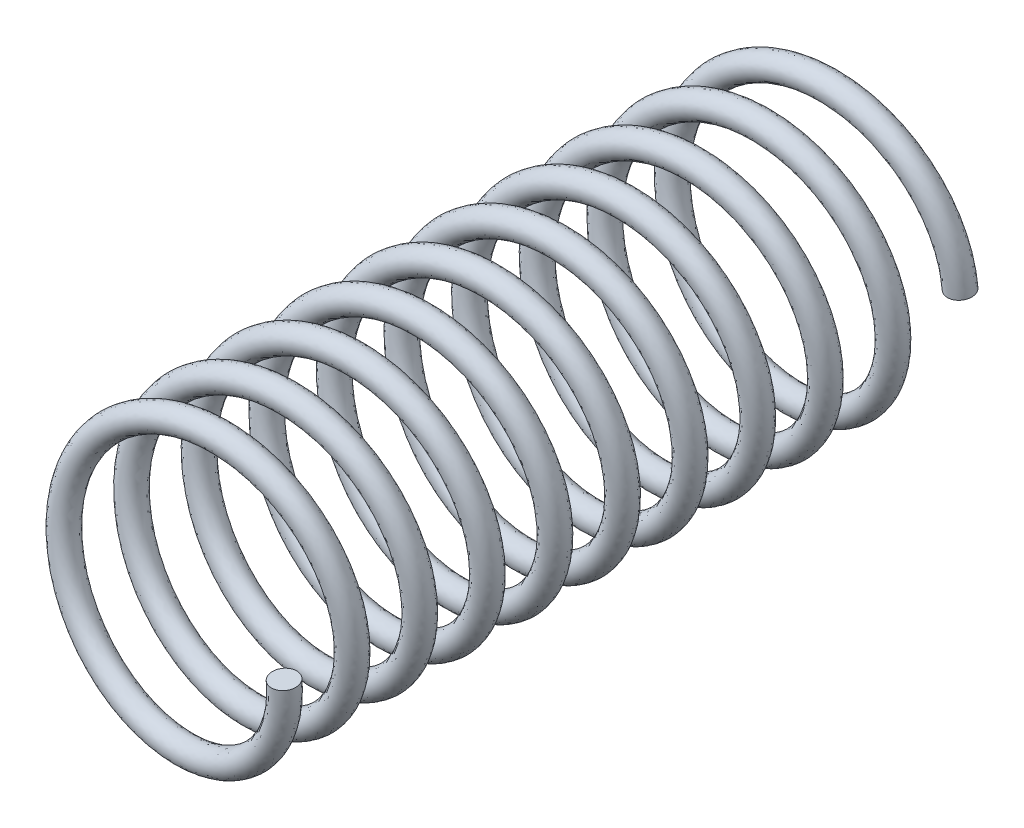
SolidWorks part; units mm, degrees
ref_plane "前视基准面" through (0, 0, 0) normal (0, 0, 1) x (1, 0, 0)
ref_plane "上视基准面" through (0, 0, 0) normal (0, 1, 0) x (1, 0, 0)
ref_plane "右视基准面" through (0, 0, 0) normal (1, 0, 0) x (0, 0, -1)
other "Configuration Table"
sketch "草图1" plane through (0, 0, 0) normal (0, 0, 1) x (1, 0, 0)
  circle A0 centre (0, 0) radius 15
curve "螺旋线/涡状线1" pitch 8 height 80 turns 10
sweep "扫描1" add path "螺旋线/涡状线1" circular profile diameter 3 parameters "D3"=3
